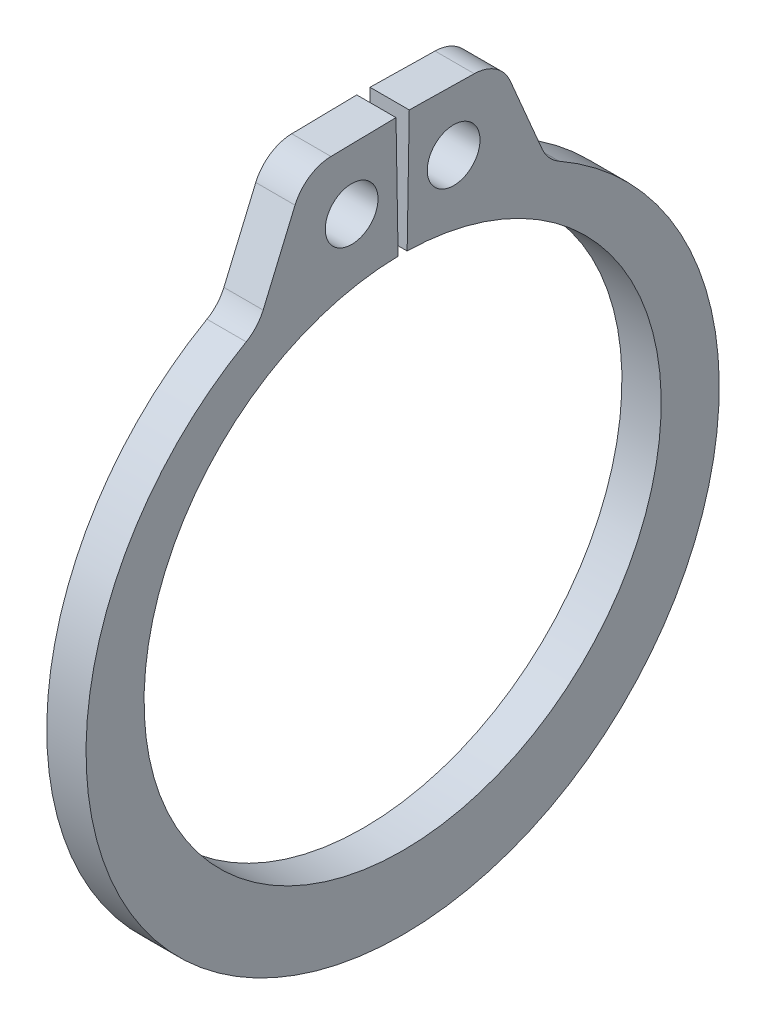
SolidWorks part; units mm, degrees
material "AISI 1020"
ref_plane "Front Plane" through (0, 0, 0) normal (0, 0, 1) x (1, 0, 0)
ref_plane "Top Plane" through (0, 0, 0) normal (0, 1, 0) x (1, 0, 0)
ref_plane "Right Plane" through (0, 0, 0) normal (1, 0, 0) x (0, 0, -1)
ref_plane "Plane1" through (-0.4445, 0, 0) normal (-1, 0, 0) x (0, -1, 0)
sketch "Sketch1" plane through (-0.4445, 0, 0) normal (-1, 0, 0) x (0, -1, 0)
  line L0 (-8.5709, 1.6222) -> (-8.5966, 0.1501)
  line L1 (-8.5966, 0.1501) -> (-5.8538, 0.1022)
  line L2 (-5.8538, -0.1022) -> (-8.5966, -0.1501)
  line L3 (-8.5966, -0.1501) -> (-8.5709, -1.6222)
  line L4 (-8.0224, -2.4362) -> (-6.3262, -3.158)
  line L5 (-6.3262, 3.158) -> (-8.0224, 2.4362)
  circle A0 centre (-7.2072, -1.1547) radius 0.5969
  arc A1 (-8.0224, 2.4362) -> (-8.5709, 1.6222) centre (-7.6693, 1.6065) ccw
  arc A2 (-5.8538, 0.1022) -> (-5.8538, -0.1022) centre (0, 0) cw
  arc A3 (-8.5709, -1.6222) -> (-8.0224, -2.4362) centre (-7.6693, -1.6065) ccw
  arc A4 (-6.3262, -3.158) -> (-5.8953, -3.5422) centre (-6.6792, -3.9877) cw
  arc A5 (-5.8953, -3.5422) -> (-5.8953, 3.5422) centre (0.3371, 0) ccw
  arc A6 (-5.8953, 3.5422) -> (-6.3262, 3.158) centre (-6.6792, 3.9877) cw
  circle A7 centre (-7.2072, 1.1547) radius 0.5969
extrude "Boss-Extrude1" add sketch "Sketch1" against normal blind 0.889
